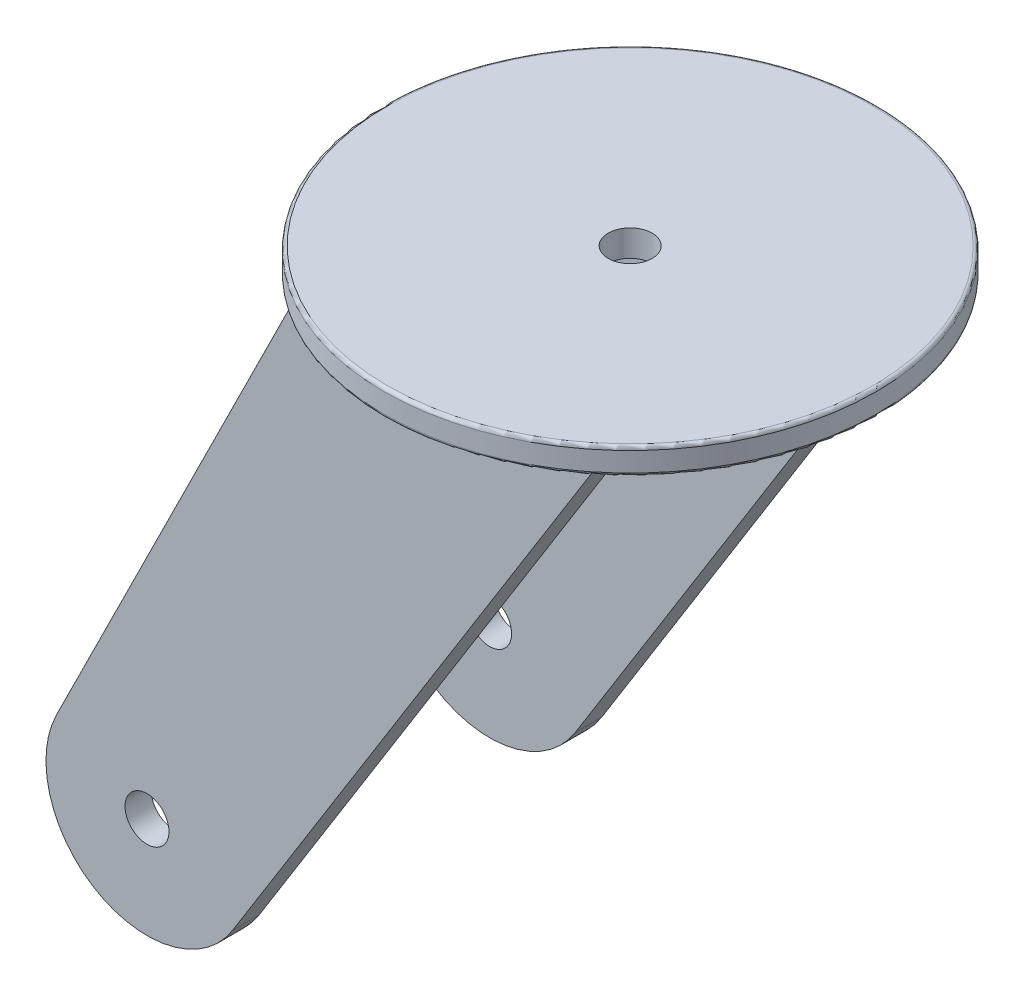
SolidWorks part; units mm, degrees
ref_plane "Front Plane" through (0, 0, 0) normal (0, 0, 1) x (1, 0, 0)
ref_plane "Top Plane" through (0, 0, 0) normal (0, 1, 0) x (1, 0, 0)
ref_plane "Right Plane" through (0, 0, 0) normal (1, 0, 0) x (0, 0, -1)
sketch "Sketch1" plane through (0, 0, 0) normal (0, 1, 0) x (1, 0, 0)
  circle A0 centre (0, 0) radius 71.12
  dimension "D1" = 142.24
extrude "Boss-Extrude1" add sketch "Sketch1" along normal blind 7.62
fillet "Fillet1" radius 0.9906 2 edges at (0, 7.62, 71.12) (0, 0, 71.12)
ref_plane "Plane1" through (0, 0, 45.72) normal (0, 0, 1) x (1, 0, 0)
sketch "Sketch3" plane through (0, 0, 45.72) normal (0, 0, 1) x (1, 0, 0)
  line L0 (0, 0) -> (43.18, 0)
  line L1 (-70.1294, 0) -> (70.1294, 0) construction
  line L2 (0, 0) -> (-43.18, 0)
  line L3 (43.18, 0) -> (-61.5796, -167.8647)
  line L4 (-43.18, 0) -> (-112.5134, -139.3913)
  arc A0 (-112.5134, -139.3913) -> (-61.5796, -167.8647) centre (-86.36, -152.4) ccw
  circle A1 centre (-86.36, -152.4) radius 6.35
  point P7 (48.26, 0)
  dimension "D3" = 58.42
  dimension "D4" = 152.4
  dimension "D5" = 129.54
  dimension "D6" = 12.7
  dimension "D1" = 43.18
  dimension "D2" = 43.18
extrude "Boss-Extrude2" add sketch "Sketch3" along normal blind 7.62
mirror "Mirror1" about plane through (0, 0, 0) normal (0, 0, 1) of "Boss-Extrude2"
sketch "Sketch5" plane through (0, 7.62, 0) normal (0, 1, 0) x (1, 0, 0)
  circle A0 centre (0, 0) radius 6.35
  dimension "D1" = 12.7
extrude "Cut-Extrude1" cut sketch "Sketch5" against normal through all
